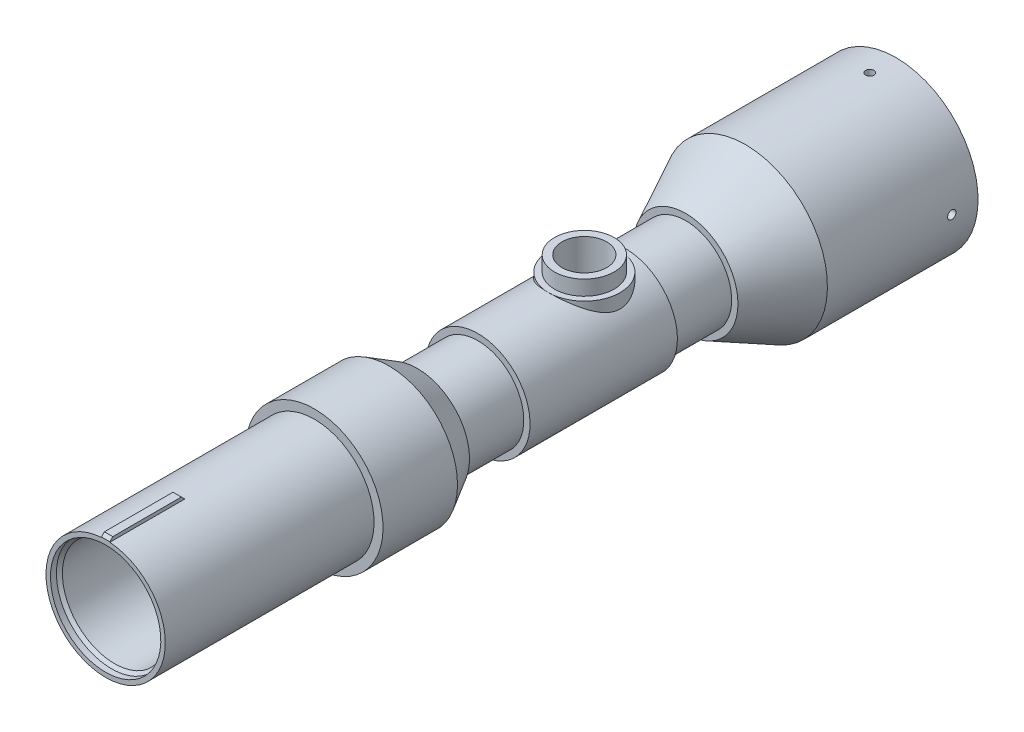
SolidWorks part; units mm, degrees
ref_plane "정면" through (0, 0, 0) normal (0, 0, 1) x (1, 0, 0)
ref_plane "윗면" through (0, 0, 0) normal (0, 1, 0) x (1, 0, 0)
ref_plane "우측면" through (0, 0, 0) normal (1, 0, 0) x (0, 0, -1)
sketch "스케치1" plane through (0, 0, 0) normal (1, 0, 0) x (0, 0, -1)
  line L0 (70, 23) -> (94.9737, 23)
  line L1 (94.9737, 23) -> (104.5, 17.5)
  line L2 (104.5, 17.5) -> (194.5, 17.5)
  line L3 (194.5, 17.5) -> (214.5, 27.5)
  line L4 (214.5, 27.5) -> (265, 27.5)
  line L5 (265, 27.5) -> (265, 0) construction
  line L6 (265, 0) -> (0, 0) construction
  line L7 (0, 0) -> (0, 23) construction
  line L8 (265, 27.5) -> (265, 25.5)
  line L9 (258.5, 25) -> (252.5, 25)
  line L10 (3, 17.5) -> (91.1763, 17.5)
  line L11 (258.5, 25) -> (262, 25.5)
  line L12 (262, 25.5) -> (265, 25.5)
  line L13 (3, 17.5) -> (2, 18.5)
  line L14 (2, 18.5) -> (0, 18.5)
  line L15 (252, 23) -> (248, 23)
  line L16 (248, 23) -> (248, 24.5) construction
  line L17 (248, 24.5) -> (133.8, 24.5) construction
  line L18 (243.5, 24.5) -> (214.5, 24.5)
  line L19 (214.5, 24.5) -> (194.5, 12)
  line L20 (194.5, 12) -> (138.8, 12)
  line L21 (133.8, 12) -> (133.8, 11)
  line L22 (133.8, 11) -> (136.8, 11)
  line L23 (0, 18.5) -> (0, 20)
  line L24 (109.65, 12) -> (109.65, 11)
  line L25 (106.65, 11) -> (109.65, 11)
  line L26 (106.65, 11) -> (91.1763, 17.5)
  line L27 (194.5, 17.5) -> (194.5, 12) construction
  line L28 (214.5, 27.5) -> (214.5, 24.5) construction
  line L29 (248, 23) -> (243.5, 24.5)
  line L30 (243.5, 24.5) -> (248, 24.5) construction
  line L31 (70, 23) -> (70, 20)
  line L32 (70, 20) -> (0, 20)
  line L33 (0, 23) -> (70, 23) construction
  line L34 (136.8, 11) -> (138.8, 12)
  line L35 (133.8, 12) -> (109.65, 12)
  line L36 (248, 24.5) -> (253.8, 24.5) construction
  line L37 (253.8, 24.5) -> (253.8, 25) construction
  line L38 (133.8, 24.5) -> (133.8, 12) construction
  arc A0 (252, 23) -> (252.5, 25) centre (263.1145, 21.2839) cw
  point P2 (252.5, 25)
  point P23 (253.8, 25)
  point P33 (158.8, 24.5)
  point P37 (0, 0)
  dimension "D2" = 50
  dimension "D3" = 4
  dimension "D4" = 35
  dimension "D5" = 46
  dimension "D6" = 3
  dimension "D7" = 2
  dimension "D8" = 0.5
  dimension "D9" = 3
  dimension "D10" = 24
  dimension "D11" = 3
  dimension "D12" = 265
  dimension "D13" = 2
  dimension "D14" = 3
  dimension "D15" = 6
  dimension "D16" = 22
  dimension "D17" = 1.3
  dimension "D18" = 95
  dimension "D19" = 120
  dimension "D20" = 35
  dimension "D21" = 70
  dimension "D22" = 150
  dimension "D23" = 30.15
  dimension "D24" = 2
  dimension "D25" = 40
  dimension "D26" = 3.5
  dimension "D27" = 4.5
  dimension "D28" = 20
  dimension "D30" = 90
  dimension "D31" = 55
  dimension "D32" = 1
  dimension "D33" = 2
  dimension "D34" = 1
revolve "회전1" add sketch "스케치1" angle 360 about L6
sketch "스케치2" plane through (0, 0, 0) normal (0, 1, 0) x (1, 0, 0)
  line L0 (0, 160.5) -> (0, 0) construction
  line L1 (-25, 255.5) -> (0, 255.5) construction
  line L2 (-25, 258.5) -> (-25, 252.5) construction
  line L3 (0, 214.5) -> (0, 265) construction
  line L4 (0, 255.5) -> (0, 160.5) construction
  circle A0 centre (0, 160.5) radius 7.5
  dimension "D1" = 15
  dimension "D2" = 95
extrude "컷-돌출1" cut sketch "스케치2" along normal mid plane 50
ref_plane "평면1" through (0, 17.5, 0) normal (0, 1, 0) x (1, 0, 0)
sketch "스케치3" plane through (0, 17.5, 0) normal (0, 1, 0) x (1, 0, 0)
  circle A0 centre (0, 160.5) radius 7.5
  circle A1 centre (0, 160.5) radius 10
  dimension "D1" = 15
  dimension "D2" = 20
extrude "보스-돌출1" add sketch "스케치3" along normal mid plane 10
sketch "스케치4" plane through (0, 0, 0) normal (1, 0, 0) x (0, 0, -1)
  line L0 (194.5, 17.5) -> (194.5, 15.4)
  line L1 (19.25, 17.5) -> (-19.25, 17.5) construction
  line L2 (194.5, 17.5) -> (194.5, -17.5) construction
  line L3 (194.5, 15.4) -> (174.2, 15.4)
  line L4 (174.2, 15.4) -> (174.2, 17.5)
  line L5 (174.2, 17.5) -> (194.5, 17.5)
  line L6 (80.5973, 17.5) -> (104.5, 15.4)
  line L7 (104.5, 17.5) -> (104.5, -17.5) construction
  line L8 (104.5, 15.4) -> (124.8, 15.4)
  line L9 (124.8, 15.4) -> (124.8, 17.5)
  line L10 (124.8, 17.5) -> (80.5973, 17.5)
  dimension "D1" = 20.3
  dimension "D2" = 20.3
  dimension "D3" = 2.1
  dimension "D4" = 2.1
revolve "컷-회전1" cut sketch "스케치4" angle 360 about axis through (0, 0, -265) along (0, 0, -1)
sketch "스케치5" plane through (0, 17.5, 0) normal (0, 1, 0) x (1, 0, 0)
  circle A0 centre (0, 160.5) radius 10
  circle A1 centre (0, 160.5) radius 12
  dimension "D1" = 20
  dimension "D2" = 24
extrude "보스-돌출2" add sketch "스케치5" against normal blind 5.5
sketch "스케치6" plane through (0, 0, 0) normal (0, 1, 0) x (1, 0, 0)
  line L0 (0, 53.6666) -> (0, 35.3005) construction
  line L1 (0, 3) -> (0, 104.5) construction
  line L2 (2.7, 53.6666) -> (2.7, 35.3005)
  line L3 (-2.7, 53.6666) -> (-2.7, 35.3005)
  arc A0 (2.7, 53.6666) -> (-2.7, 53.6666) centre (0, 53.6666) ccw
  arc A1 (-2.7, 35.3005) -> (2.7, 35.3005) centre (0, 35.3005) ccw
  point P5 (0, 44.4835)
  dimension "D1" = 2.7
extrude "컷-돌출2" cut sketch "스케치6" against normal blind 30
sketch "스케치7" plane through (0, 0, 0) normal (0, 0, 1) x (1, 0, 0)
  line L1 (-1.4, 21.1) -> (1.4, 21.1)
  line L2 (-1.4, 21.1) -> (-1.4, 18.9)
  line L3 (-1.4, 18.9) -> (1.4, 18.9)
  line L4 (1.4, 21.1) -> (1.4, 18.9)
  line L5 (-1.4, 21.1) -> (1.4, 18.9) construction
  line L6 (-1.4, 18.9) -> (1.4, 21.1) construction
  line L7 (0, 22.5) -> (0, 12) construction
  line L8 (0, 20) -> (0, 0) construction
  circle A0 centre (0, 0) radius 20 construction
  circle A1 centre (0, 0) radius 20 construction
  point P0 (0, 20)
  dimension "D1" = 2.8
  dimension "D2" = 2.2
extrude "보스-돌출3" add sketch "스케치7" against normal blind 25
chamfer "모따기1" distance 1 angle 45 2 edges at (0, 21.1, 0) (0, 21.1, -25)
ref_plane "평면2" through (0, 0, -125) normal (0, 0, 1) x (1, 0, 0)
sketch "스케치8" plane through (0, 0, -125) normal (0, 0, 1) x (1, 0, 0)
  line L1 (-50.3448, -38.0185) -> (50.3448, -38.0185)
  line L2 (-50.3448, -38.0185) -> (-50.3448, 38.0185)
  line L3 (-50.3448, 38.0185) -> (50.3448, 38.0185)
  line L4 (50.3448, -38.0185) -> (50.3448, 38.0185)
  line L5 (-50.3448, -38.0185) -> (50.3448, 38.0185) construction
  line L6 (-50.3448, 38.0185) -> (50.3448, -38.0185) construction
  point P0 (0, 0)
sketch "스케치10" plane through (0, 0, 0) normal (1, 0, 0) x (0, 0, -1)
  line L0 (214.5, 0) -> (265, 0) construction
  line L1 (265, -27.5) -> (265, 27.5) construction
  circle A0 centre (256.2, 0) radius 1.4
  dimension "D1" = 2.8
  dimension "D2" = 8.8
extrude "컷-돌출3" cut sketch "스케치10" against normal through all both and the other way through all contours A0
sketch "스케치11" plane through (0, 0, 0) normal (0, 1, 0) x (1, 0, 0)
  line L0 (-27.3856, 256.2) -> (0, 256.2) construction
  line L1 (-27.5, 256.2) -> (-25, 256.2) construction
  line L2 (0, 214.5) -> (0, 265) construction
  circle A0 centre (0, 256.2) radius 1.4
  dimension "D1" = 2.8
extrude "컷-돌출4" cut sketch "스케치11" against normal through all both and the other way through all
